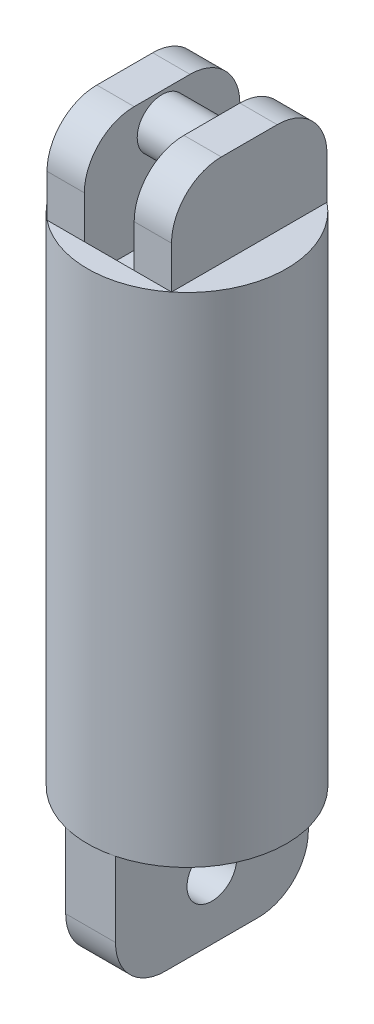
SolidWorks part; units mm, degrees
ref_plane "Front Plane" through (0, 0, 0) normal (0, 0, 1) x (1, 0, 0)
ref_plane "Top Plane" through (0, 0, 0) normal (0, 1, 0) x (1, 0, 0)
ref_plane "Right Plane" through (0, 0, 0) normal (1, 0, 0) x (0, 0, -1)
sketch "Sketch1" plane through (0, 0, 0) normal (0, 1, 0) x (1, 0, 0)
  circle A0 centre (0, 0) radius 50.8
  dimension "D1" = 101.6
extrude "Boss-Extrude1" add sketch "Sketch1" along normal blind 254
sketch "Sketch2" plane through (0, 254, 0) normal (0, 1, 0) x (1, 0, 0)
  line L1 (-31.75, -39.6557) -> (31.75, -39.6557)
  line L2 (-31.75, -39.6557) -> (-31.75, 39.6557)
  line L3 (-31.75, 39.6557) -> (31.75, 39.6557)
  line L4 (31.75, -39.6557) -> (31.75, 39.6557)
  line L5 (-31.75, -39.6557) -> (31.75, 39.6557) construction
  line L6 (-31.75, 39.6557) -> (31.75, -39.6557) construction
  circle A0 centre (0, 0) radius 50.8 construction
  point P0 (0, 0)
  dimension "D1" = 63.5
extrude "Boss-Extrude2" add sketch "Sketch2" along normal blind 46.99
sketch "Sketch3" plane through (0, 300.99, 0) normal (0, 1, 0) x (1, 0, 0)
  line L0 (31.75, 39.6557) -> (-31.75, 39.6557) construction
  line L1 (-12.7, -39.6557) -> (12.7, -39.6557)
  line L2 (-12.7, -39.6557) -> (-12.7, 39.6557)
  line L3 (-12.7, 39.6557) -> (12.7, 39.6557)
  line L4 (12.7, -39.6557) -> (12.7, 39.6557)
  line L5 (-12.7, -39.6557) -> (12.7, 39.6557) construction
  line L6 (-12.7, 39.6557) -> (12.7, -39.6557) construction
  point P0 (0, 0)
  dimension "D1" = 25.4
extrude "Cut-Extrude1" cut sketch "Sketch3" against normal blind 63.5
fillet "Fillet1" radius 25.4 4 edges at (-22.225, 300.99, -39.6557) (-22.225, 300.99, 39.6557) (22.225, 300.99, -39.6557) (22.225, 300.99, 39.6557)
sketch "Sketch6" plane through (31.75, 0, 0) normal (1, 0, 0) x (0, 0, -1)
  circle A0 centre (0, 286.4944) radius 12.7
sketch "Sketch7" plane through (0, 0, 0) normal (0, -1, 0) x (1, 0, 0)
  line L1 (-12.7, -49.1869) -> (12.7, -49.1869)
  line L2 (-12.7, -49.1869) -> (-12.7, 49.1869)
  line L3 (-12.7, 49.1869) -> (12.7, 49.1869)
  line L4 (12.7, -49.1869) -> (12.7, 49.1869)
  line L5 (-12.7, -49.1869) -> (12.7, 49.1869) construction
  line L6 (-12.7, 49.1869) -> (12.7, -49.1869) construction
  circle A0 centre (0, 0) radius 50.8 construction
  point P0 (0, 0)
  dimension "D1" = 25.4
extrude "Boss-Extrude3" add sketch "Sketch7" along normal blind 63.5
sketch "Sketch8" plane through (12.7, 0, 0) normal (1, 0, 0) x (0, 0, -1)
  circle A0 centre (0, -31.75) radius 12.7
extrude "Cut-Extrude5" cut sketch "Sketch8" against normal through all
fillet "Fillet2" radius 25.4 2 edges at (0, -63.5, 49.1869) (0, -63.5, -49.1869)
extrude "Boss-Extrude4" add sketch "Sketch6" against normal blind 53.34
